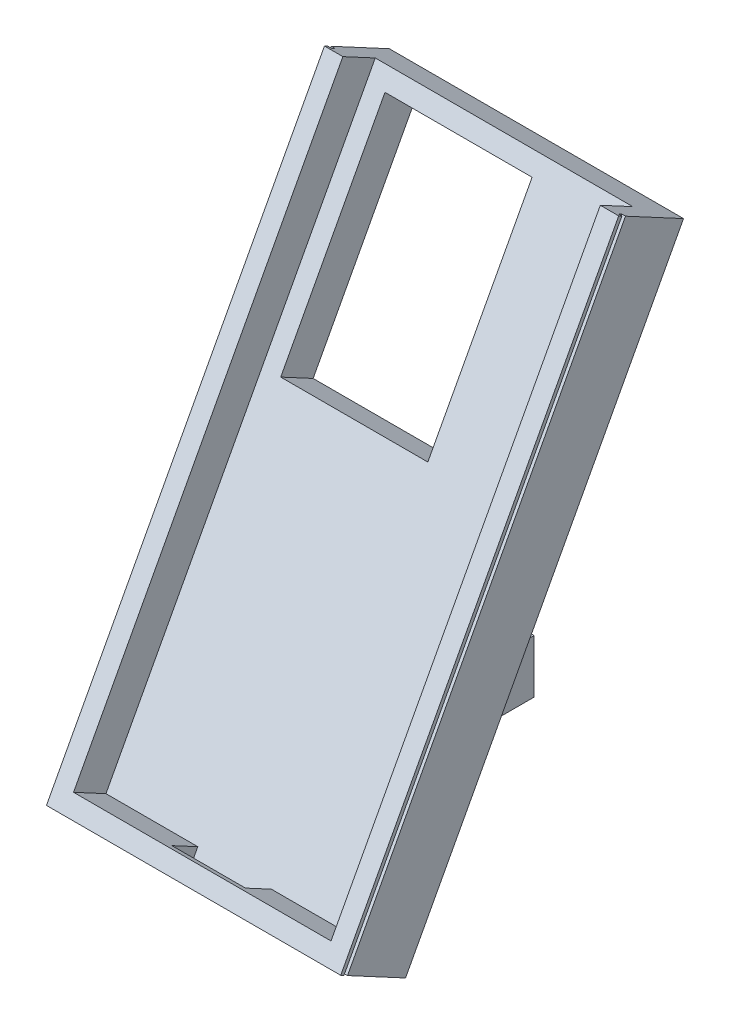
SolidWorks part; units mm, degrees
ref_plane "前视基准面" through (0, 0, 0) normal (0, 0, 1) x (1, 0, 0)
ref_plane "上视基准面" through (0, 0, 0) normal (0, 1, 0) x (1, 0, 0)
ref_plane "右视基准面" through (0, 0, 0) normal (1, 0, 0) x (0, 0, -1)
sketch "草图1" plane through (0, 0, 0) normal (0, 0, 1) x (1, 0, 0)
  line L1 (-19.75, -7.25) -> (19.75, -7.25)
  line L2 (-19.75, -7.25) -> (-19.75, 7.25)
  line L3 (-19.75, 7.25) -> (19.75, 7.25)
  line L4 (19.75, -7.25) -> (19.75, 7.25)
  line L5 (-19.75, -7.25) -> (19.75, 7.25) construction
  line L6 (-19.75, 7.25) -> (19.75, -7.25) construction
  point P0 (0, 0)
  dimension "D1" = 39.5
  dimension "D2" = 14.5
extrude "凸台-拉伸1" add sketch "草图1" along normal blind 40
sketch "草图2" plane through (-19.75, 0, 0) normal (-1, 0, 0) x (0, 0, 1)
  line L0 (40, -7.25) -> (32.2284, 7.25)
  line L1 (40, 7.25) -> (0, 7.25) construction
sketch "草图3" plane through (0, 7.25, 0) normal (0, 1, 0) x (1, 0, 0)
  line L0 (-19.75, -32.2284) -> (19.75, -32.2284)
  line L1 (-19.75, -40) -> (-19.75, -32.2284) construction
  line L2 (-19.75, -40) -> (-19.75, 0) construction
  line L3 (19.75, -40) -> (19.75, 0) construction
sketch "草图4" plane through (19.75, 0, 0) normal (1, 0, 0) x (0, 0, -1)
  line L0 (-32.2284, 7.25) -> (-40, -7.25)
ref_plane "基准面4" through (0, 15.0367, 28.0549) normal (0, 0.4724, 0.8814) x (1, 0, 0)
sketch "草图6" plane through (0, 15.0367, 28.0549) normal (0, 0.4724, 0.8814) x (1, 0, 0)
  line L1 (-40, -57.5147) -> (40, -57.5147)
  line L2 (-40, -57.5147) -> (-40, 102.4853)
  line L3 (-40, 102.4853) -> (40, 102.4853)
  line L4 (40, -57.5147) -> (40, 102.4853)
  line L5 (-40, -57.5147) -> (40, 102.4853) construction
  line L6 (-40, 102.4853) -> (40, -57.5147) construction
  point P0 (0, 22.4853)
  point P5 (3.1952, 18.1084)
  point P6 (0.4003, 8.356)
  point P7 (0, 30.7594)
  point P8 (0, 22.6078)
  point P9 (0, 22.4853)
  dimension "D1" = 80
  dimension "D2" = 160
extrude "凸台-拉伸2" add sketch "草图6" along normal blind 10
sketch "草图7" plane through (0, 19.7607, 36.8688) normal (0, 0.4724, 0.8814) x (1, 0, 0)
  line L0 (40, 102.4853) -> (-40, 102.4853) construction
  line L1 (-35, -52.5147) -> (35, -52.5147)
  line L2 (-35, -52.5147) -> (-35, 102.4853)
  line L4 (35, -52.5147) -> (35, 102.4853)
  line L5 (-35, 102.4853) -> (-40, 102.4853)
  line L6 (-40, 102.4853) -> (-40, -57.5147)
  line L7 (-40, -57.5147) -> (40, -57.5147)
  line L8 (40, -57.5147) -> (40, 102.4853)
  line L9 (40, 102.4853) -> (35, 102.4853)
  point P0 (0, 38.9439)
  dimension "D1" = 5
  dimension "D2" = 5
  dimension "D3" = 5
extrude "凸台-拉伸3" add sketch "草图7" along normal blind 10
sketch "草图8" plane through (0, 19.7607, 36.8688) normal (0, 0.4724, 0.8814) x (1, 0, 0)
  line L1 (-30, 37.4853) -> (10, 37.4853)
  line L2 (-30, 37.4853) -> (-30, 97.4853)
  line L3 (-30, 97.4853) -> (10, 97.4853)
  line L4 (10, 37.4853) -> (10, 97.4853)
  line L5 (-30, 37.4853) -> (10, 97.4853) construction
  line L6 (-30, 97.4853) -> (10, 37.4853) construction
  line L7 (-35, -52.5147) -> (-35, 102.4853) construction
  line L8 (35, 102.4853) -> (-35, 102.4853) construction
  point P0 (-10, 67.4853)
  point P7 (-0.2719, 53.406)
  dimension "D1" = 5
  dimension "D2" = 40
  dimension "D3" = 60
  dimension "D4" = 5
extrude "切除-拉伸1" cut sketch "草图8" against normal blind 10
sketch "草图9" plane through (0, -50.6926, 27.1698) normal (0, -0.8814, 0.4724) x (1, 0, 0)
  line L0 (-40, 51.8305) -> (40, 51.8305) construction
  line L1 (-10.0273, 41.8305) -> (9.9727, 41.8305)
  line L2 (-10.0273, 41.8305) -> (-10.0273, 49.8305)
  line L3 (-10.0273, 49.8305) -> (9.9727, 49.8305)
  line L4 (9.9727, 41.8305) -> (9.9727, 49.8305)
  line L5 (-10.0273, 41.8305) -> (9.9727, 49.8305) construction
  line L6 (-10.0273, 49.8305) -> (9.9727, 41.8305) construction
  point P0 (-0.0273, 45.8305)
  point P5 (0.5899, 43.2014)
  point P6 (0, 42.0147)
  point P9 (0, 0)
  dimension "D1" = 20
  dimension "D2" = 8
  dimension "D3" = 2
extrude "切除-拉伸3" cut sketch "草图9" against normal blind 10
sketch "草图10" plane through (-40, 0, 0) normal (-1, 0, 0) x (0, 0, 1)
  line L0 (-3.6126, 114.3413) -> (71.9711, -26.6803)
  line L1 (-2.7313, 114.8137) -> (-20.359, 105.3658) construction
  line L2 (72.8525, -26.2079) -> (55.2248, -35.6559) construction
  line L3 (71.0016, -27.1999) -> (-4.5822, 113.8217)
  line L4 (-4.5822, 113.8217) -> (-3.6126, 114.3413)
  line L5 (-2.7313, 114.8137) -> (72.8525, -26.2079) construction
  dimension "D1" = 1
  dimension "D2" = 1.1
extrude "切除-拉伸4" cut sketch "草图10" against normal blind 1 and the other way through all flip side to cut
sketch "草图11" plane through (40, 0, 0) normal (1, 0, 0) x (0, 0, -1)
  line L0 (3.6126, 114.3413) -> (-71.9711, -26.6803)
  line L1 (2.7313, 114.8137) -> (20.359, 105.3658) construction
  line L2 (-72.8525, -26.2079) -> (-55.2248, -35.6559) construction
  line L3 (-71.9711, -26.6803) -> (-71.0016, -27.1999)
  line L4 (-71.0016, -27.1999) -> (4.5822, 113.8217)
  line L5 (4.5822, 113.8217) -> (3.6126, 114.3413)
  line L6 (-72.8525, -26.2079) -> (2.7313, 114.8137) construction
  dimension "D1" = 1
  dimension "D2" = 1.1
extrude "切除-拉伸5" cut sketch "草图11" against normal blind 1
